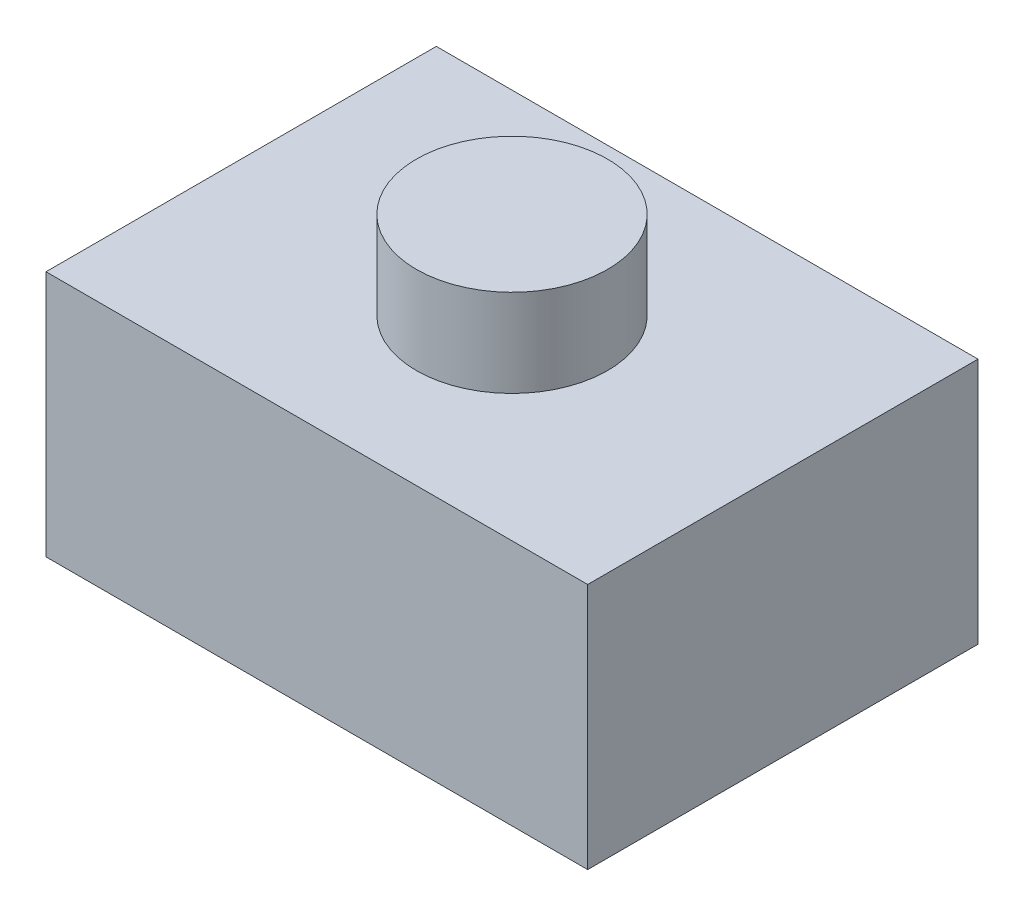
SolidWorks part; units mm, degrees
ref_plane "前视基准面" through (0, 0, 0) normal (0, 0, 1) x (1, 0, 0)
ref_plane "上视基准面" through (0, 0, 0) normal (0, 1, 0) x (1, 0, 0)
ref_plane "右视基准面" through (0, 0, 0) normal (1, 0, 0) x (0, 0, -1)
other "Configuration Table"
sketch "草图1" plane through (0, 0, 0) normal (0, 1, 0) x (1, 0, 0)
  line L1 (0, 0) -> (-34, 0)
  line L2 (0, 0) -> (0, 24.5)
  line L3 (0, 24.5) -> (-34, 24.5)
  line L4 (-34, 0) -> (-34, 24.5)
  dimension "D1" = 24.5
  dimension "D2" = 34
extrude "凸台-拉伸1" add sketch "草图1" along normal blind 15.5
sketch "草图2" plane through (0, 15.5, 0) normal (0, 1, 0) x (1, 0, 0)
  line L0 (-34, 24.5) -> (0, 0) construction
  circle A0 centre (-17, 12.25) radius 6
  dimension "D1" = 12
extrude "凸台-拉伸2" add sketch "草图2" along normal blind 5.5
